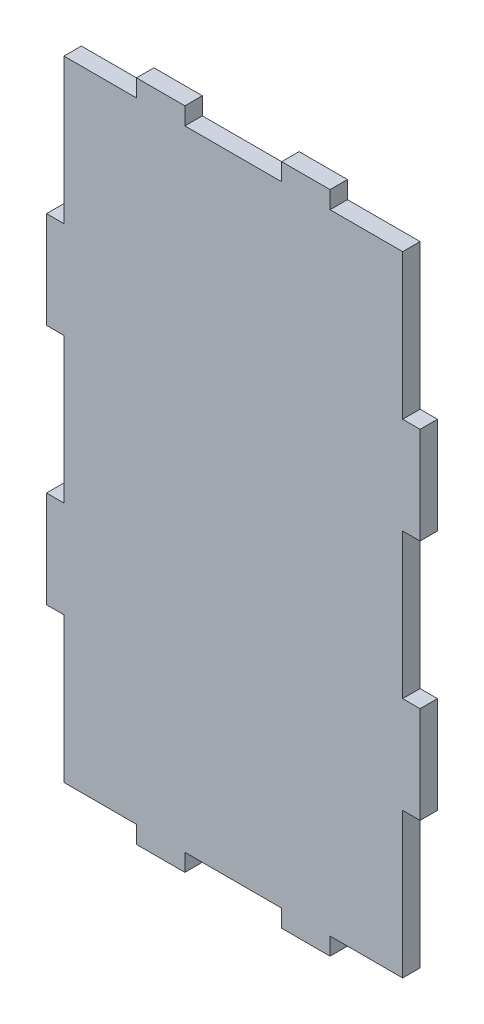
SolidWorks part; units mm, degrees
ref_plane "Front Plane" through (0, 0, 0) normal (0, 0, 1) x (1, 0, 0)
ref_plane "Top Plane" through (0, 0, 0) normal (0, 1, 0) x (1, 0, 0)
ref_plane "Right Plane" through (0, 0, 0) normal (1, 0, 0) x (0, 0, -1)
sketch "Sketch1" plane through (0, 0, 0) normal (0, 0, 1) x (1, 0, 0)
  line L1 (0, 0) -> (98.044, 0)
  line L2 (0, 0) -> (0, 174.244)
  line L3 (0, 174.244) -> (98.044, 174.244)
  line L4 (98.044, 0) -> (98.044, 174.244)
  dimension "D1" = 98.044
  dimension "D2" = 174.244
extrude "Boss-Extrude1" add sketch "Sketch1" along normal blind 4.572
sketch "Sketch2" plane through (0, 0, 4.572) normal (0, 0, 1) x (1, 0, 0)
  line L0 (0, 0) -> (98.044, 0) construction
  line L1 (0, 0) -> (23.622, 0)
  line L2 (0, 0) -> (0, 4.572)
  line L3 (0, 4.572) -> (23.622, 4.572)
  line L4 (23.622, 0) -> (23.622, 4.572)
  line L5 (36.322, 0) -> (61.722, 0)
  line L6 (36.322, 0) -> (36.322, 4.572)
  line L7 (36.322, 4.572) -> (61.722, 4.572)
  line L8 (61.722, 0) -> (61.722, 4.572)
  line L9 (98.044, 174.244) -> (0, 174.244) construction
  line L10 (98.044, 0) -> (74.422, 0)
  line L11 (98.044, 0) -> (98.044, 4.572)
  line L12 (98.044, 4.572) -> (74.422, 4.572)
  line L13 (74.422, 0) -> (74.422, 4.572)
  line L14 (0, 174.244) -> (23.622, 174.244)
  line L15 (0, 174.244) -> (0, 169.672)
  line L16 (0, 169.672) -> (23.622, 169.672)
  line L17 (23.622, 174.244) -> (23.622, 169.672)
  line L18 (36.322, 174.244) -> (61.722, 174.244)
  line L19 (36.322, 174.244) -> (36.322, 169.672)
  line L20 (36.322, 169.672) -> (61.722, 169.672)
  line L21 (61.722, 174.244) -> (61.722, 169.672)
  line L23 (98.044, 174.244) -> (74.422, 174.244)
  line L24 (98.044, 174.244) -> (98.044, 169.672)
  line L25 (98.044, 169.672) -> (74.422, 169.672)
  line L26 (74.422, 174.244) -> (74.422, 169.672)
  dimension "D1" = 4.572
  dimension "D2" = 4.572
  dimension "D3" = 4.572
  dimension "D4" = 12.7
  dimension "D5" = 23.622
  dimension "D6" = 23.622
  dimension "D7" = 25.4
  dimension "D8" = 4.572
  dimension "D9" = 4.572
  dimension "D10" = 4.572
  dimension "D11" = 25.4
  dimension "D12" = 12.7
  dimension "D13" = 23.622
  dimension "D14" = 23.622
extrude "Cut-Extrude1" cut sketch "Sketch2" against normal blind 4.572
sketch "Sketch3" plane through (0, 0, 4.572) normal (0, 0, 1) x (1, 0, 0)
  line L0 (0, 169.672) -> (0, 4.572) construction
  line L1 (0, 4.572) -> (4.572, 4.572)
  line L2 (0, 4.572) -> (0, 42.672)
  line L3 (0, 42.672) -> (4.572, 42.672)
  line L4 (4.572, 4.572) -> (4.572, 42.672)
  line L5 (98.044, 4.572) -> (93.472, 4.572)
  line L6 (98.044, 4.572) -> (98.044, 42.672)
  line L7 (98.044, 42.672) -> (93.472, 42.672)
  line L8 (93.472, 4.572) -> (93.472, 42.672)
  line L9 (0, 106.172) -> (4.572, 106.172)
  line L10 (0, 106.172) -> (0, 68.072)
  line L11 (0, 68.072) -> (4.572, 68.072)
  line L12 (4.572, 106.172) -> (4.572, 68.072)
  line L13 (98.044, 4.572) -> (98.044, 169.672) construction
  line L14 (0, 169.672) -> (4.572, 169.672)
  line L15 (0, 169.672) -> (0, 131.572)
  line L16 (0, 131.572) -> (4.572, 131.572)
  line L17 (4.572, 169.672) -> (4.572, 131.572)
  line L18 (98.044, 169.672) -> (93.472, 169.672)
  line L19 (98.044, 169.672) -> (98.044, 131.572)
  line L20 (98.044, 131.572) -> (93.472, 131.572)
  line L21 (93.472, 169.672) -> (93.472, 131.572)
  line L22 (98.044, 106.172) -> (93.472, 106.172)
  line L23 (98.044, 106.172) -> (98.044, 68.072)
  line L24 (98.044, 68.072) -> (93.472, 68.072)
  line L25 (93.472, 106.172) -> (93.472, 68.072)
  point P32 (2.286, 42.672)
  dimension "D1" = 38.1
  dimension "D2" = 38.1
  dimension "D3" = 38.1
  dimension "D4" = 38.1
  dimension "D5" = 38.1
  dimension "D6" = 38.1
  dimension "D7" = 25.4
  dimension "D8" = 25.4
  dimension "D9" = 4.572
  dimension "D10" = 4.572
  dimension "D11" = 4.572
  dimension "D12" = 4.572
  dimension "D13" = 4.572
  dimension "D14" = 4.572
extrude "Cut-Extrude2" cut sketch "Sketch3" against normal blind 4.572
